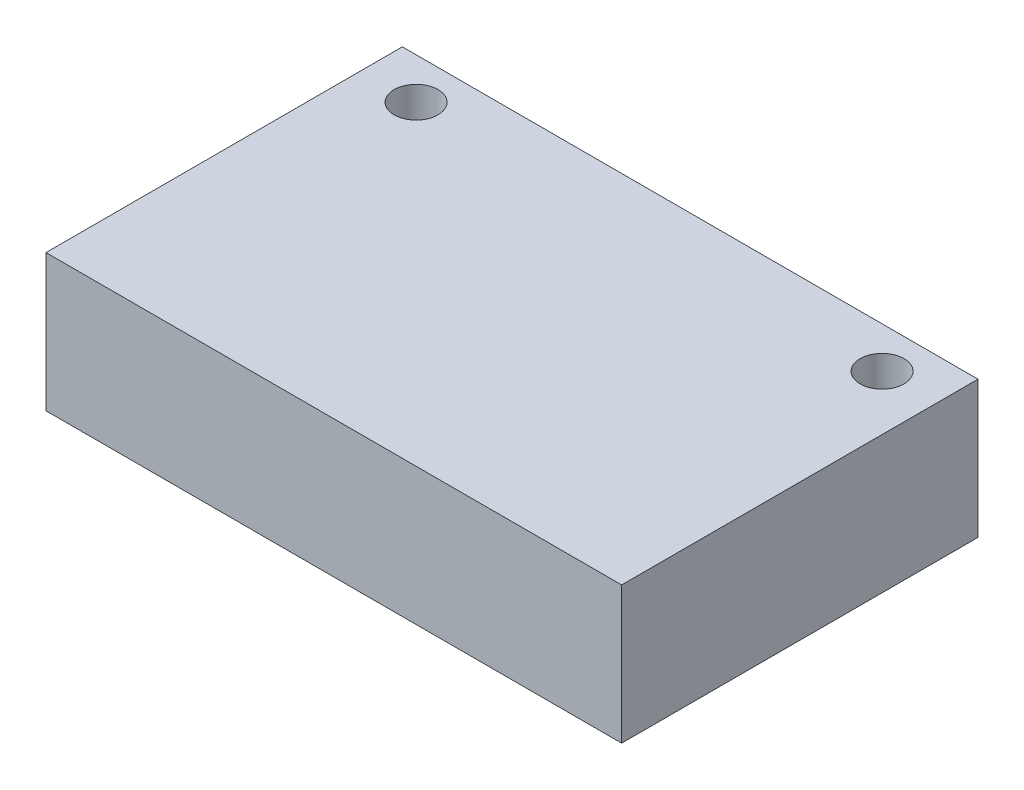
SolidWorks part; units mm, degrees
ref_plane "Alzado" through (0, 0, 0) normal (0, 0, 1) x (1, 0, 0)
ref_plane "Planta" through (0, 0, 0) normal (0, 1, 0) x (1, 0, 0)
ref_plane "Vista lateral" through (0, 0, 0) normal (1, 0, 0) x (0, 0, -1)
sketch "Croquis2" plane through (0, 0, 0) normal (0, 1, 0) x (1, 0, 0)
  line L1 (-21, 13) -> (21, 13)
  line L2 (-21, 13) -> (-21, -13)
  line L3 (-21, -13) -> (21, -13)
  line L4 (21, 13) -> (21, -13)
  line L5 (-21, 13) -> (21, -13) construction
  line L6 (-21, -13) -> (21, 13) construction
  circle A0 centre (-17, 10) radius 1.6
  circle A1 centre (17, 10) radius 1.6
  point P0 (0, 0)
  dimension "D3" = 3.2
  dimension "D4" = 3.2
  dimension "D1" = 42
  dimension "D2" = 26
  dimension "D5" = 4
  dimension "D6" = 4
  dimension "D7" = 3
  dimension "D8" = 3
extrude "Saliente-Extruir1" add sketch "Croquis2" along normal blind 10
